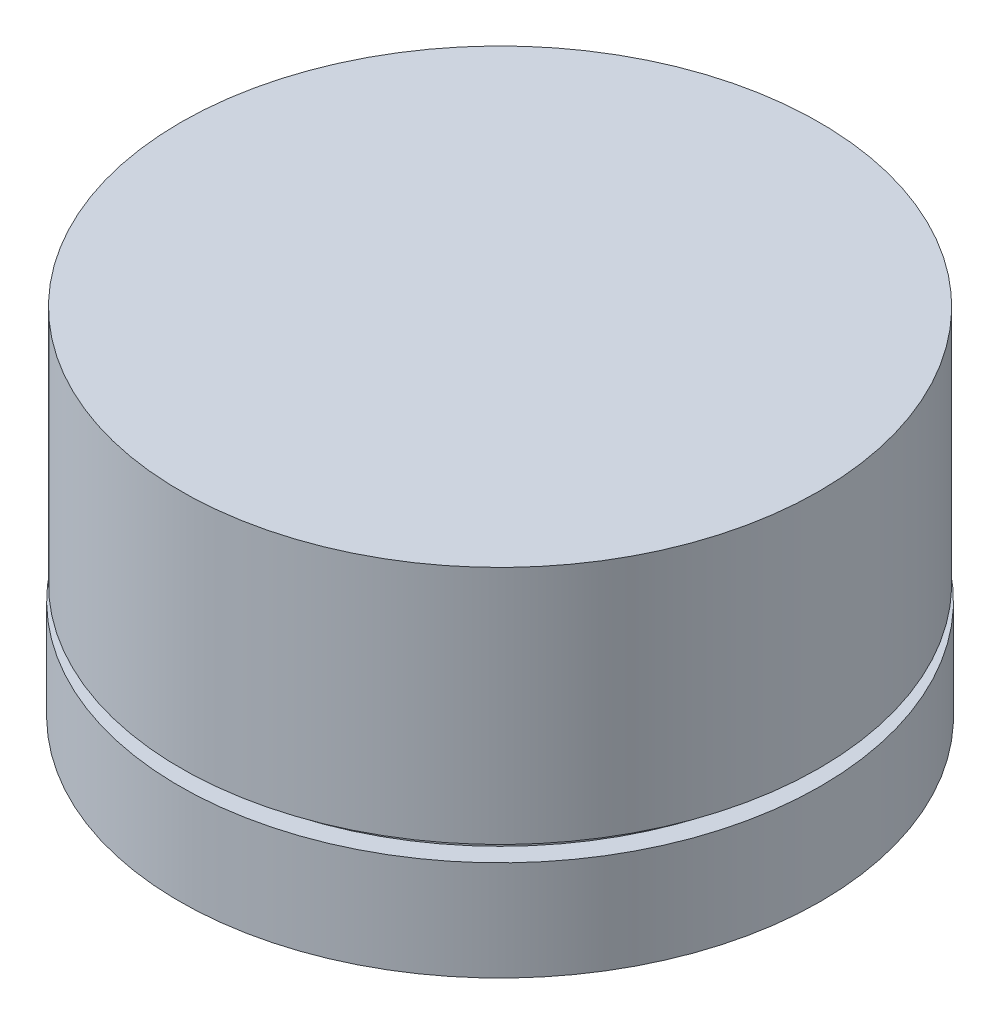
SolidWorks part; units mm, degrees
ref_plane "Front Plane" through (0, 0, 0) normal (0, 0, 1) x (1, 0, 0)
ref_plane "Top Plane" through (0, 0, 0) normal (0, 1, 0) x (1, 0, 0)
ref_plane "Right Plane" through (0, 0, 0) normal (1, 0, 0) x (0, 0, -1)
sketch "Sketch1" plane through (0, 0, 0) normal (0, 0, 1) x (1, 0, 0)
  line L0 (0, 0) -> (0, 19) construction
  line L1 (0, 19) -> (16, 19)
  line L2 (16, 19) -> (16, 6.9788)
  line L3 (16, 6.9788) -> (15.0501, 6.9788)
  line L5 (15.0501, 6.9788) -> (15.0501, 6.2288)
  line L7 (15.0501, 6.2288) -> (16.0641, 6.2288)
  line L9 (16.0641, 6.2288) -> (16.0641, 1.2288)
  line L10 (16.0641, 1.2288) -> (13, 1.2288)
  line L11 (13, 1.2288) -> (13, 4.2288)
  line L12 (13, 4.2288) -> (14.5, 4.2288)
  line L14 (14.5, 4.2288) -> (14.5, 8.2288)
  line L15 (14.5, 8.2288) -> (14, 8.2288)
  line L16 (14, 8.2288) -> (14, 18)
  line L17 (14, 18) -> (0, 18)
  line L18 (0, 18) -> (0, 19)
  point P15 (12.7222, 17.4415)
  point P16 (13.5425, 3.9476)
  point P17 (0, 0)
  point P18 (12.7222, 0.742)
  point P19 (12.5684, 0.5478)
  point P20 (13.7866, 3.9476)
  point P21 (12.7222, 17.4415)
  point P22 (14.9506, 7.3312)
  point P23 (16.0035, 7.3312)
  point P24 (0, 0)
  point P25 (13.9236, 7.7036)
  point P26 (14.0302, 17.731)
  point P27 (14.0342, 18.001)
  point P28 (13.0045, 3.7053)
  point P29 (0, 0)
  point P30 (0, 0)
  point P31 (16.2149, 6.7319)
  point P32 (16.2149, 7.4819)
  point P33 (0, 0)
  point P34 (16.2149, 0.7048)
  point P35 (0, 0)
  dimension "D1" = 32
  dimension "D2" = 28
  dimension "D3" = 26
  dimension "D4" = 3
  dimension "D5" = 29
  dimension "D6" = 19
  dimension "D7" = 1
  dimension "D8" = 5
  dimension "D10" = 0.75
  dimension "D11" = 4
revolve "Revolve1" add sketch "Sketch1" angle 360 about L0
